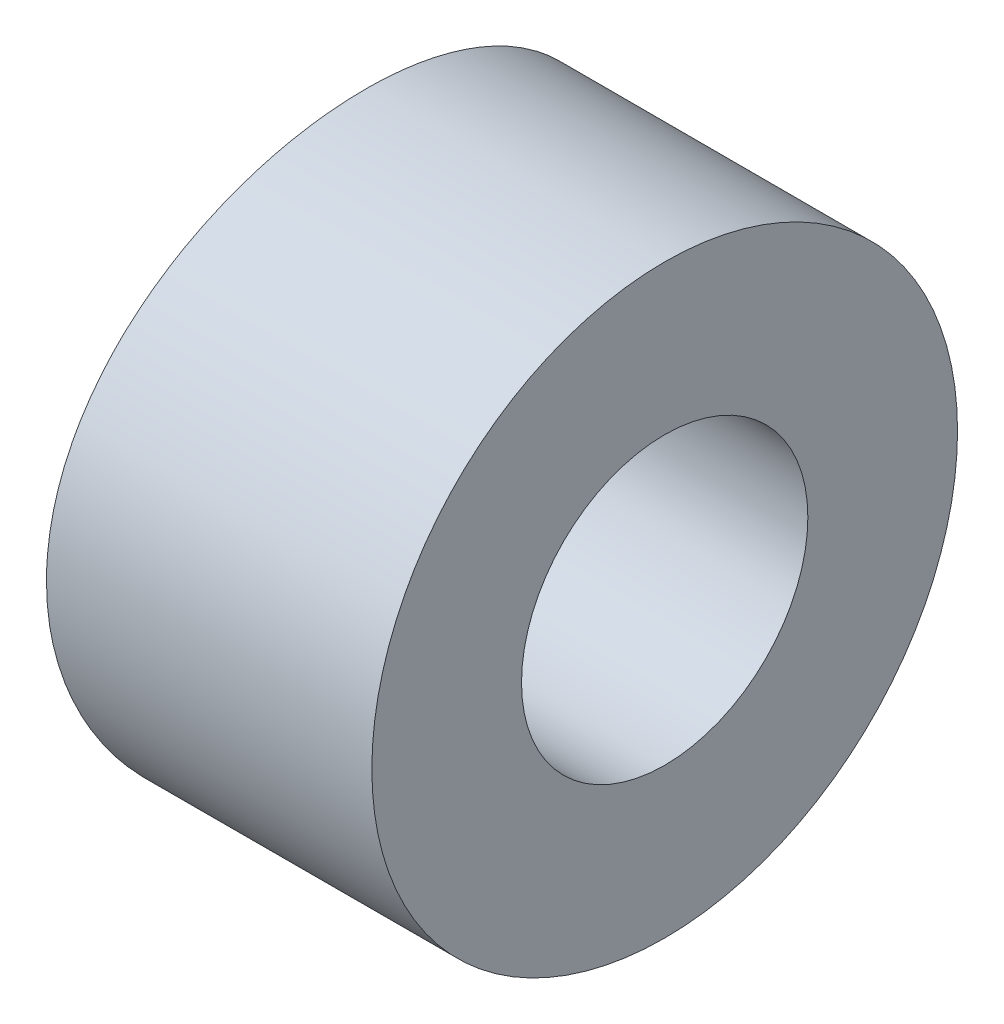
SolidWorks part; units mm, degrees
material "ABS"
ref_plane "Front Plane" through (0, 0, 0) normal (0, 0, 1) x (1, 0, 0)
ref_plane "Top Plane" through (0, 0, 0) normal (0, 1, 0) x (1, 0, 0)
ref_plane "Right Plane" through (0, 0, 0) normal (1, 0, 0) x (0, 0, -1)
sketch "Sketch1" plane through (0, 0, 0) normal (1, 0, 0) x (0, 0, -1)
  circle A0 centre (0, 0) radius 2.25
  circle A2 centre (0, 0) radius 1.1
  dimension "D1" = 4.5
  dimension "D2" = 2.2
extrude "Boss-Extrude1" add sketch "Sketch1" along normal blind 2.5
sketch "Sketch4" plane through (0, 0, 0) normal (0, 1, 0) x (1, 0, 0)
  line L0 (0, 2.25) -> (0, -2.25) construction
  line L1 (2.5, 2.25) -> (0, 2.25) construction
  line L2 (0, 2.25) -> (0, -2.25)
  arc A0 (0, -2.25) -> (0, 2.25) centre (-12.4991, 0) ccw
  dimension "D1" = 12.7
extrude "Cut-Extrude1" cut sketch "Sketch4" against normal through all both and the other way through all contours L2 A0
